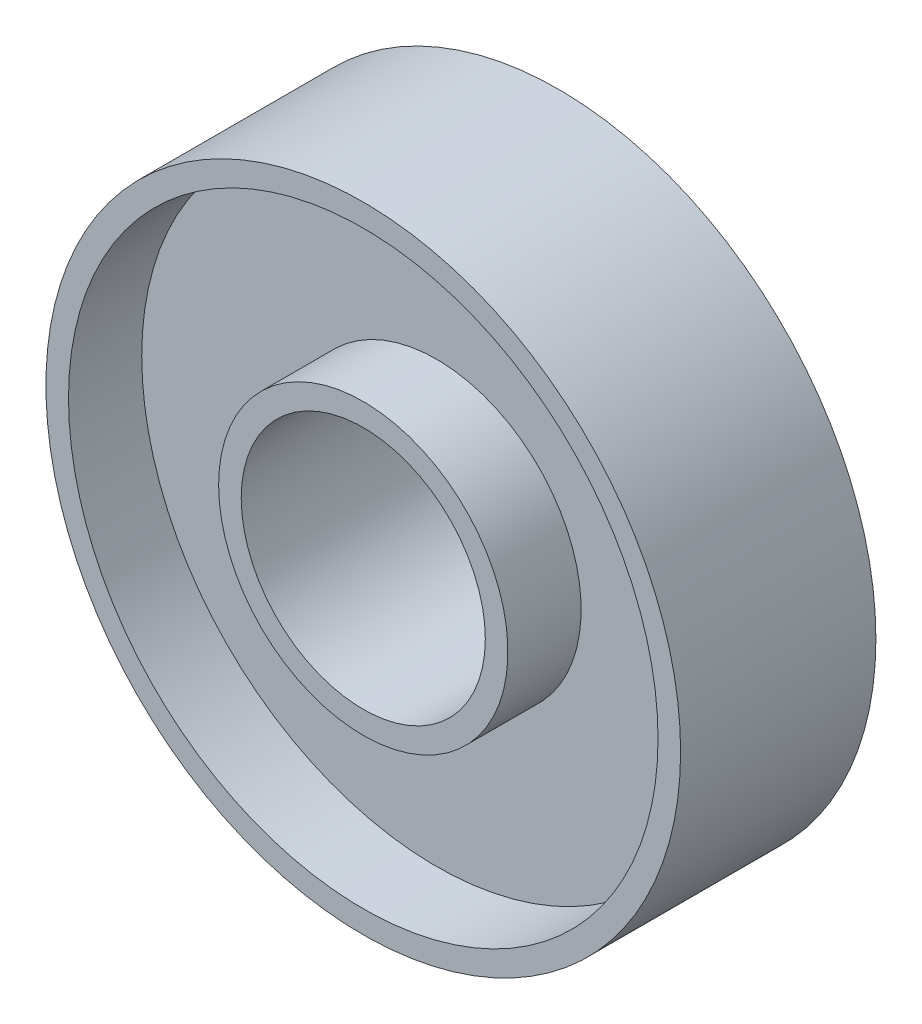
SolidWorks part; units mm, degrees
ref_plane "Front Plane" through (0, 0, 0) normal (0, 0, 1) x (1, 0, 0)
ref_plane "Top Plane" through (0, 0, 0) normal (0, 1, 0) x (1, 0, 0)
ref_plane "Right Plane" through (0, 0, 0) normal (1, 0, 0) x (0, 0, -1)
sketch "Sketch2" plane through (0, 0, 0) normal (0, 0, 1) x (1, 0, 0)
  circle A0 centre (0, 0) radius 12.075
  circle A1 centre (0, 0) radius 13
  dimension "D1" = 26
  dimension "D2" = 24.15
extrude "Boss-Extrude1" add sketch "Sketch2" along normal blind 8
ref_plane "Plane1" through (0, 0, 4) normal (0, 0, -1) x (-1, 0, 0)
sketch "Sketch3" plane through (0, 0, 4) normal (0, 0, -1) x (-1, 0, 0)
  circle A0 centre (0, 0) radius 12.5695
extrude "Boss-Extrude2" add sketch "Sketch3" along normal blind 1 and the other way blind 1
sketch "Sketch5" plane through (0, 0, 4) normal (0, 0, -1) x (-1, 0, 0)
  circle A0 centre (0, 0) radius 5
  circle A1 centre (0, 0) radius 5.925
  dimension "D1" = 10
  dimension "D2" = 11.85
extrude "Boss-Extrude3" add sketch "Sketch5" along normal blind 4 and the other way blind 4
sketch "Sketch6" plane through (0, 0, 5) normal (0, 0, 1) x (1, 0, 0)
  circle A0 centre (0, 0) radius 5
extrude "Cut-Extrude1" cut sketch "Sketch6" against normal blind 2
